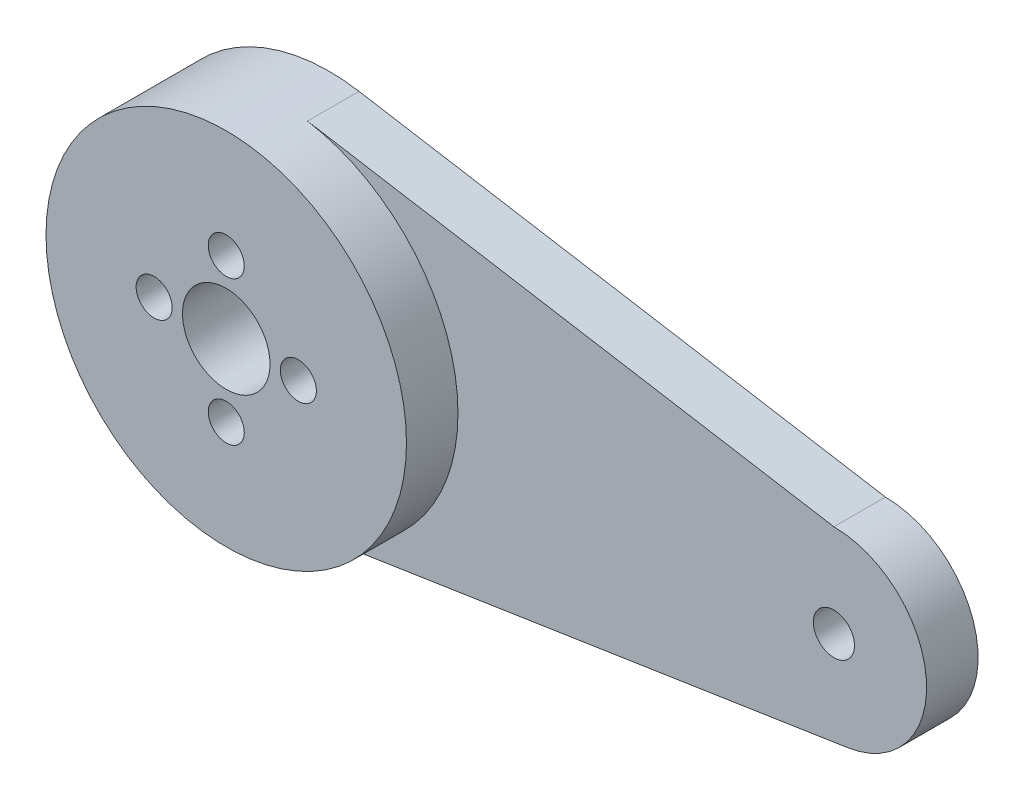
SolidWorks part; units mm, degrees
ref_plane "Front Plane" through (0, 0, 0) normal (0, 0, 1) x (1, 0, 0)
ref_plane "Top Plane" through (0, 0, 0) normal (0, 1, 0) x (1, 0, 0)
ref_plane "Right Plane" through (0, 0, 0) normal (1, 0, 0) x (0, 0, -1)
sketch "Sketch1" plane through (0, 0, 0) normal (0, 0, 1) x (1, 0, 0)
  line L0 (-20.22, 57.58) -> (33.78, 57.2783) construction
  line L1 (-20.22, 57.58) -> (33.78, 57.2783) construction
  circle A0 centre (-20.22, 57.58) radius 17.5 construction
  circle A1 centre (-20.22, 57.58) radius 17.5
sketch "Sketch2" plane through (0, 0, 0) normal (0, 0, 1) x (1, 0, 0)
  line L0 (-17.3289, 74.8395) -> (33.78, 66.2783)
  line L1 (35.147, 48.3828) -> (-17.562, 40.283)
  circle A0 centre (33.78, 57.2783) radius 9 construction
  circle A1 centre (-20.22, 57.58) radius 17.5 construction
  arc A2 (-17.3289, 74.8395) -> (-17.562, 40.283) centre (-20.22, 57.58) ccw
  arc A3 (33.78, 66.2783) -> (35.147, 48.3828) centre (33.78, 57.2783) cw
  circle A4 centre (-20.22, 57.58) radius 4.25
  circle A5 centre (33.78, 57.2783) radius 2
  dimension "D1" = 18
  dimension "D2" = 4
  dimension "D3" = 8.5
extrude "Boss-Extrude1" add sketch "Sketch2" against normal blind 5
sketch "草图1" plane through (0, 0, 0) normal (0, 0, 1) x (1, 0, 0)
  line L0 (-20.22, 50.58) -> (-20.22, 64.58) construction
  line L1 (-13.22, 57.58) -> (-27.22, 57.58) construction
  circle A0 centre (-13.22, 57.58) radius 1.75
  circle A1 centre (-27.22, 57.58) radius 1.75
  circle A2 centre (-20.22, 64.58) radius 1.75
  circle A3 centre (-20.22, 50.58) radius 1.75
  circle A5 centre (-20.22, 57.58) radius 4.25 construction
  point P10 (-20.22, 57.58)
  point P11 (-20.22, 57.58)
  dimension "D1" = 3.5
  dimension "D2" = 14
  dimension "D3" = 14
extrude "切除-拉伸1" cut sketch "草图1" against normal blind 10
sketch "草图2" plane through (0, 0, 0) normal (0, 0, 1) x (1, 0, 0)
  circle A0 centre (-20.22, 57.58) radius 17.5
  circle A1 centre (-20.22, 64.58) radius 1.75 construction
  circle A2 centre (-13.22, 57.58) radius 1.75 construction
  circle A3 centre (-20.22, 50.58) radius 1.75 construction
  circle A4 centre (-27.22, 57.58) radius 1.75 construction
  circle A5 centre (-27.22, 57.58) radius 1.75
  circle A6 centre (-20.22, 50.58) radius 1.75
  circle A7 centre (-13.22, 57.58) radius 1.75
  circle A8 centre (-20.22, 64.58) radius 1.75
  circle A9 centre (-20.22, 57.58) radius 4.25 construction
  circle A10 centre (-20.22, 57.58) radius 4.25
extrude "凸台-拉伸1" add sketch "草图2" along normal blind 5
